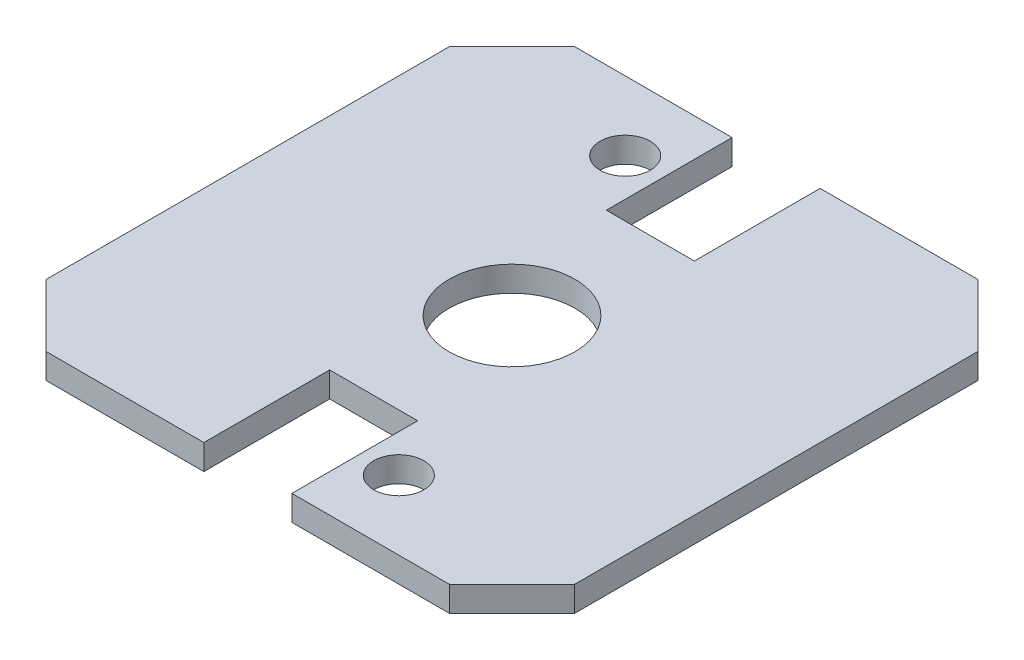
SolidWorks part; units mm, degrees
ref_plane "Front Plane" through (0, 0, 0) normal (0, 0, 1) x (1, 0, 0)
ref_plane "Top Plane" through (0, 0, 0) normal (0, 1, 0) x (1, 0, 0)
ref_plane "Right Plane" through (0, 0, 0) normal (1, 0, 0) x (0, 0, -1)
sketch "Sketch1" plane through (0, 0, 0) normal (0, 1, 0) x (1, 0, 0)
  line L1 (-21, -21) -> (21, -21)
  line L2 (-21, -21) -> (-21, 21)
  line L3 (-21, 21) -> (21, 21)
  line L4 (21, -21) -> (21, 21)
  line L5 (-21, -21) -> (21, 21) construction
  line L6 (-21, 21) -> (21, -21) construction
  point P0 (0, 0)
  dimension "D1" = 42
  dimension "D2" = 42
extrude "Boss-Extrude1" add sketch "Sketch1" along normal blind 2
sketch "Sketch2" plane through (0, 2, 0) normal (0, 1, 0) x (1, 0, 0)
  line L0 (-21, 21) -> (-21, -21)
  line L1 (-21, 21) -> (21, 21)
  line L2 (-21, -21) -> (21, -21)
  line L3 (21, 21) -> (21, -21)
  line L4 (-21, 16.0503) -> (-16.0503, 21)
  line L5 (16.0503, 21) -> (21, 16.0503)
  line L6 (21, -16.0503) -> (16.0503, -21)
  line L7 (-16.0503, -21) -> (-21, -16.0503)
  line L8 (-6.8918, 0) -> (8.4391, 0) construction
  line L9 (0, 0) -> (6.4536, 6.4536) construction
  line M11 (21, -21) -> (21, 21)
  line M12 (21, 21) -> (-21, 21)
  line M13 (-21, 21) -> (-21, -21)
  line M14 (-21, -21) -> (21, -21)
  dimension "D1" = 7
  dimension "D2" = 45
  dimension "D3" = 42
extrude "Cut-Extrude1" cut sketch "Sketch2" against normal blind 10 contours L4 L1 M13 | L5 L3 M12 | L6 L2 M11 | L7 M14 M13
sketch "Sketch3" plane through (0, 2, 0) normal (0, 1, 0) x (1, 0, 0)
  circle A0 centre (0, 0) radius 5
  dimension "D1" = 10
extrude "Cut-Extrude2" cut sketch "Sketch3" against normal blind 10
sketch "Sketch4" plane through (0, 0, 0) normal (0, -1, 0) x (1, 0, 0)
  line L0 (-21, -16.0503) -> (-21, 16.0503) construction
  line L1 (9, 18) -> (4, 18) construction
  line L2 (9, 18) -> (9, 13) construction
  line L3 (9, 13) -> (4, 13) construction
  line L4 (4, 18) -> (4, 13) construction
  line L5 (9, 18) -> (6.5, 15.5) construction
  line L6 (6.5, 15.5) -> (4, 18) construction
  line L7 (-9, -18) -> (-4, -18) construction
  line L8 (-9, -18) -> (-9, -13) construction
  line L9 (-9, -13) -> (-4, -13) construction
  line L10 (-4, -18) -> (-4, -13) construction
  line L11 (-9, -18) -> (-4, -13) construction
  line L12 (-9, -13) -> (-6.5, -15.5) construction
  line L13 (21, 16.0503) -> (21, -16.0503) construction
  line L14 (16.0503, -21) -> (-16.0503, -21) construction
  line L15 (-16.0503, 21) -> (16.0503, 21) construction
  line L16 (-6.5, -15.5) -> (-4, -18) construction
  line L17 (9, 13) -> (6.5, 15.5) construction
  line L18 (6.5, 15.5) -> (4, 13) construction
  circle A0 centre (6.5, 15.5) radius 2
  circle A1 centre (-6.5, -15.5) radius 2
  point P0 (6.5, 15.5)
  point P5 (-6.5, -15.5)
  dimension "D6" = 4
  dimension "D1" = 5
  dimension "D2" = 12
  dimension "D3" = 12
  dimension "D4" = 3
  dimension "D5" = 3
extrude "Cut-Extrude3" cut sketch "Sketch4" against normal blind 10
sketch "Sketch5" plane through (0, 0, 0) normal (0, -1, 0) x (1, 0, 0)
  line L0 (-16.0503, 21) -> (16.0503, 21) construction
  line L1 (-3.5, -21) -> (3.5, -21)
  line L2 (-3.5, -21) -> (-3.5, -11)
  line L3 (-3.5, 21) -> (3.5, 21)
  line L4 (3.5, -21) -> (3.5, -11)
  line L5 (-3.5, 11) -> (3.5, 11)
  line L6 (-3.5, -11) -> (3.5, -11)
  line L7 (3.5, 11) -> (3.5, 21)
  line L8 (-3.5, 11) -> (-3.5, 21)
  point P0 (0, 0)
  dimension "D1" = 7
  dimension "D2" = 10
  dimension "D3" = 10
extrude "Cut-Extrude4" cut sketch "Sketch5" against normal blind 4
